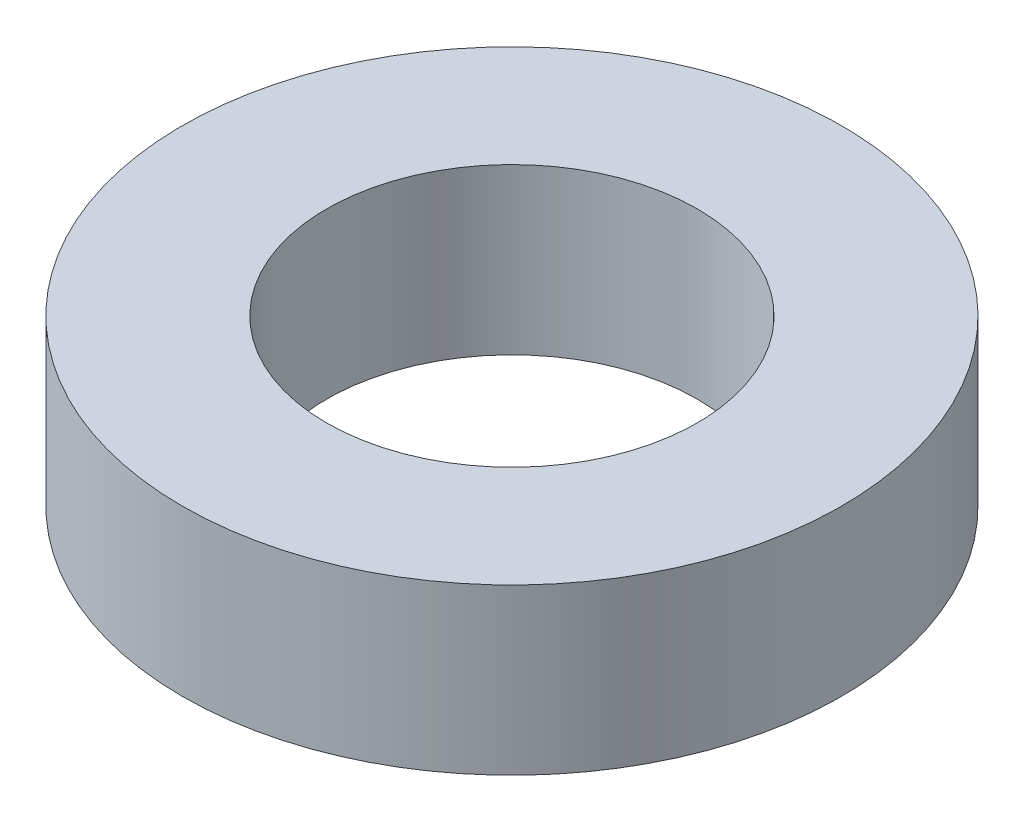
SolidWorks part; units mm, degrees
ref_plane "前视基准面" through (0, 0, 0) normal (0, 0, 1) x (1, 0, 0)
ref_plane "上视基准面" through (0, 0, 0) normal (0, 1, 0) x (1, 0, 0)
ref_plane "右视基准面" through (0, 0, 0) normal (1, 0, 0) x (0, 0, -1)
sketch "草图1" plane through (0, 0, 0) normal (0, 1, 0) x (1, 0, 0)
  circle A0 centre (0, 0) radius 8
  circle A1 centre (0, 0) radius 4.5
  dimension "D1" = 16
  dimension "D2" = 9
extrude "凸台-拉伸1" add sketch "草图1" along normal blind 4
